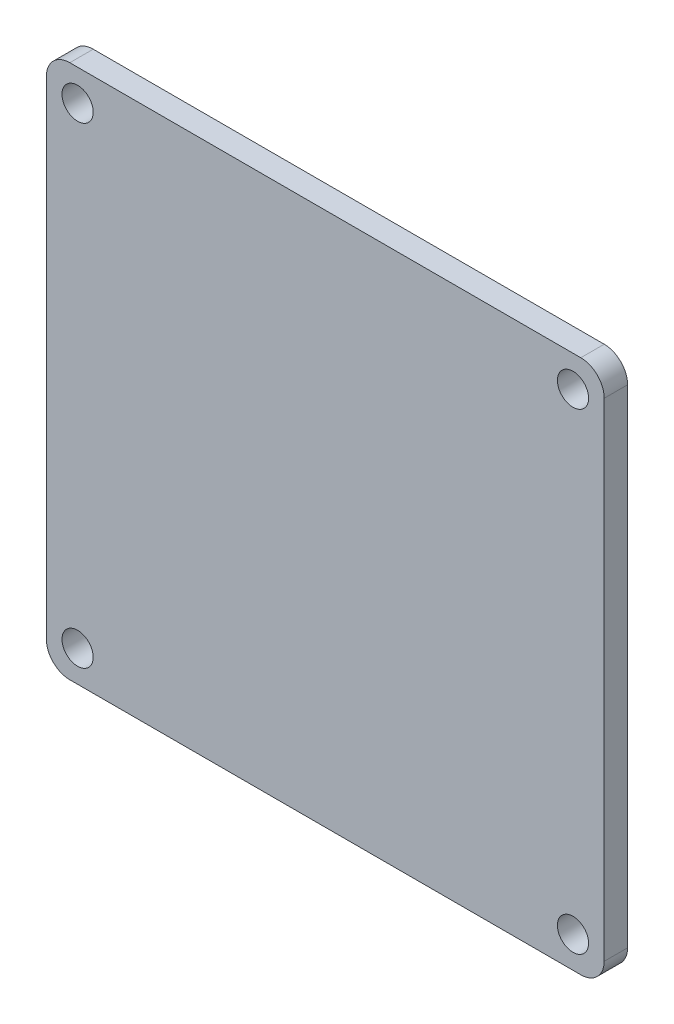
SolidWorks part; units mm, degrees
ref_plane "Front Plane" through (0, 0, 0) normal (0, 0, 1) x (1, 0, 0)
ref_plane "Top Plane" through (0, 0, 0) normal (0, 1, 0) x (1, 0, 0)
ref_plane "Right Plane" through (0, 0, 0) normal (1, 0, 0) x (0, 0, -1)
sketch "Esboço1" plane through (0, 0, 0) normal (0, 0, 1) x (1, 0, 0)
  line L0 (35.75, 68.5) -> (35.75, 0) construction
  line L1 (0, 0) -> (71.5, 0)
  line L2 (0, 0) -> (0, 68.5)
  line L3 (0, 68.5) -> (71.5, 68.5)
  line L4 (71.5, 0) -> (71.5, 68.5)
  line L5 (0, 34.25) -> (71.5, 34.25) construction
  circle A0 centre (4, 64.5) radius 2
  circle A1 centre (67.5, 64.5) radius 2
  circle A2 centre (67.5, 4) radius 2
  circle A3 centre (4, 4) radius 2
  dimension "D5" = 4
  dimension "D1" = 71.5
  dimension "D2" = 68.5
  dimension "D3" = 4
  dimension "D4" = 4
extrude "Ressalto-extrusão1" add sketch "Esboço1" along normal blind 3
fillet "Filete1" radius 3 4 edges at (71.5, 0, 1.5) (71.5, 68.5, 1.5) (0, 68.5, 1.5) (0, 0, 1.5)
